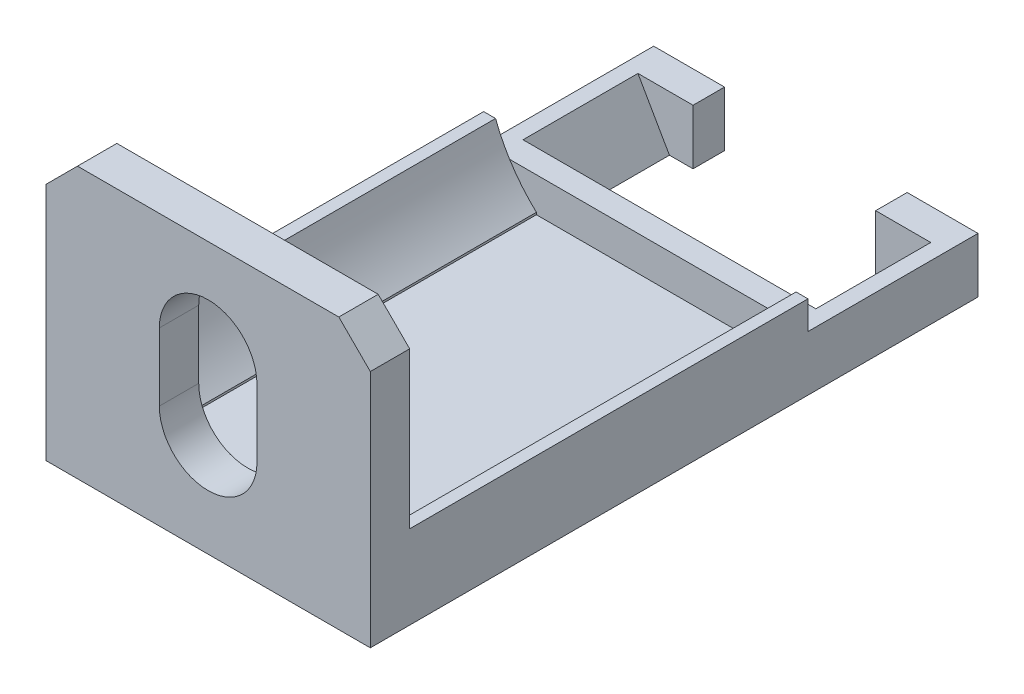
SolidWorks part; units mm, degrees
ref_plane "Front Plane" through (0, 0, 0) normal (0, 0, 1) x (1, 0, 0)
ref_plane "Top Plane" through (0, 0, 0) normal (0, 1, 0) x (1, 0, 0)
ref_plane "Right Plane" through (0, 0, 0) normal (1, 0, 0) x (0, 0, -1)
sketch "Sketch1" plane through (0, 0, 0) normal (0, 0, 1) x (1, 0, 0)
  line L0 (0, 0) -> (0, 8.6) construction
  line L1 (-10.3, -8.6) -> (10.3, -8.6)
  line L2 (-10.3, -8.6) -> (-10.3, 8.6)
  line L3 (-10.3, 8.6) -> (10.3, 8.6)
  line L4 (10.3, -8.6) -> (10.3, 8.6)
  line L5 (-10.3, -8.6) -> (10.3, 8.6) construction
  line L6 (-10.3, 8.6) -> (10.3, -8.6) construction
  line L7 (0, 2.3) -> (0, -2) construction
  line L8 (3.1, 2.3) -> (3.1, -2)
  line L9 (-3.1, 2.3) -> (-3.1, -2)
  arc A0 (3.1, 2.3) -> (-3.1, 2.3) centre (0, 2.3) ccw
  arc A1 (-3.1, -2) -> (3.1, -2) centre (0, -2) ccw
  point P0 (0, 0)
  point P10 (0, 0.15)
  dimension "D1" = 20.6
  dimension "D2" = 17.2
  dimension "D3" = 3.2
  dimension "D4" = 6.2
  dimension "D5" = 3.5
extrude "Boss-Extrude1" add sketch "Sketch1" along normal blind 2.5
sketch "Sketch2" plane through (0, 0, 0) normal (0, 0, -1) x (-1, 0, 0)
  line L0 (10.3, 8.6) -> (10.3, -8.6) construction
  line L1 (-10.3, -8.6) -> (10.3, -8.6)
  line L2 (-10.3, -8.6) -> (-10.3, -7.3)
  line L3 (-10.3, -7.3) -> (10.3, -7.3)
  line L4 (10.3, -8.6) -> (10.3, -7.3)
  dimension "D1" = 1.3
extrude "Boss-Extrude2" add sketch "Sketch2" along normal blind 25.3
sketch "Sketch3" plane through (0, 0, -25.3) normal (0, 0, -1) x (-1, 0, 0)
  line L0 (10.3, 8.6) -> (10.3, -7.3) construction
  line L1 (-10.3, -8.6) -> (10.3, -8.6)
  line L2 (-10.3, -8.6) -> (-10.3, -5.1)
  line L3 (-10.3, -5.1) -> (10.3, -5.1)
  line L4 (10.3, -8.6) -> (10.3, -5.1)
  dimension "D1" = 3.5
extrude "Boss-Extrude3" add sketch "Sketch3" along normal blind 1.5
sketch "Sketch4" plane through (0, -7.3, 0) normal (0, 1, 0) x (1, 0, 0)
  line L0 (0, 25.3) -> (0, 0) construction
  line L1 (-10.3, 25.3) -> (10.3, 25.3) construction
  line L3 (-6.95, 0) -> (6.95, 0)
  line L4 (-6.95, 0) -> (-6.95, 25.3)
  line L5 (-6.95, 25.3) -> (6.95, 25.3)
  line L6 (6.95, 0) -> (6.95, 25.3)
  line L7 (-6.95, 0) -> (6.95, 25.3) construction
  line L8 (-6.95, 25.3) -> (6.95, 0) construction
  line L9 (-10.3, 0) -> (10.3, 0)
  line L10 (-10.3, 0) -> (-10.3, 25.3)
  line L11 (-10.3, 25.3) -> (10.3, 25.3)
  line L12 (10.3, 0) -> (10.3, 25.3)
  line L13 (-10.3, 0) -> (10.3, 25.3) construction
  line L14 (-10.3, 25.3) -> (10.3, 0) construction
  point P5 (0, 12.65)
  point P10 (0, 12.65)
  line M9 (-10.3, 0) -> (10.3, 0)
  line M10 (10.3, 0) -> (10.3, 25.3)
  line M11 (10.3, 25.3) -> (-10.3, 25.3)
  line M12 (-10.3, 25.3) -> (-10.3, 0)
  dimension "D1" = 13.9
extrude "Boss-Extrude4" add sketch "Sketch4" along normal blind 4 contours L4 M9 M11 M12 | L6 M9 M10 M11
sketch "Sketch5" plane through (0, 0, 0) normal (0, 0, -1) x (-1, 0, 0)
  line L0 (6.95, -7.3) -> (-6.95, -7.3) construction
  line L1 (6.95, -7.3) -> (-6.95, -7.3)
  circle A0 centre (0, 0.3) radius 10.2
  point P5 (0, 0.7056)
  line M2 (-6.95, -3.3) -> (-6.95, -7.3)
  line M4 (6.95, -7.3) -> (6.95, -3.3)
  line M5 (6.95, -3.3) -> (10.3, -3.3)
  line M7 (10.3, 8.6) -> (-10.3, 8.6)
  line M9 (-10.3, -3.3) -> (-6.95, -3.3)
  line M10 (-3.1, -2) -> (-3.1, 2.3)
  arc M11 (-3.1, 2.3) -> (3.1, 2.3) centre (0, 2.3) cw
  line M12 (3.1, 2.3) -> (3.1, -2)
  arc M13 (3.1, -2) -> (-3.1, -2) centre (0, -2) cw
  dimension "D1" = 20.4
  dimension "D2" = 0.3
extrude "Cut-Extrude2" cut sketch "Sketch5" along normal up to surface (25.3 mm away) contours A0 L1 M7 M9 M2 M4 M5 M13 M10 M11 M12 | A0 M4 M5 | A0 M9 M2 up to face at (0, -6.2, -25.3)
chamfer "Chamfer1" distance 2 angle 45 2 edges at (-10.3, 8.6, 1.25) (10.3, 8.6, 1.25)
sketch "Sketch6" plane through (0, 0, -26.8) normal (0, 0, -1) x (-1, 0, 0)
  line L0 (-7.3, -8.6) -> (-10.3, -8.6)
  line L1 (-10.3, -8.6) -> (10.3, -8.6) construction
  line L2 (-10.3, -8.6) -> (-10.3, -5.1)
  line L3 (-10.3, -5.1) -> (-9.3, -5.1)
  line L4 (10.3, -5.1) -> (-10.3, -5.1) construction
  line L5 (-9.3, -5.1) -> (-7.3, -8.6)
  line L6 (0, -8.6) -> (0, 0) construction
  line L7 (9.3, -5.1) -> (7.3, -8.6)
  line L8 (10.3, -5.1) -> (9.3, -5.1)
  line L9 (10.3, -8.6) -> (10.3, -5.1)
  line L10 (7.3, -8.6) -> (10.3, -8.6)
  dimension "D1" = 3
  dimension "D2" = 1
extrude "Boss-Extrude5" add sketch "Sketch6" along normal blind 9.3
sketch "Sketch7" plane through (0, 0, -36.1) normal (0, 0, -1) x (-1, 0, 0)
  line L0 (0, -8.6) -> (0, 0) construction
  line L1 (-10.3, -8.6) -> (-5.8, -8.6)
  line L2 (-10.3, -8.6) -> (-10.3, -5.1)
  line L3 (-10.3, -5.1) -> (-5.8, -5.1)
  line L4 (-5.8, -8.6) -> (-5.8, -5.1)
  line L5 (-7.3, -8.6) -> (7.3, -8.6) construction
  line L6 (5.8, -8.6) -> (5.8, -5.1)
  line L7 (10.3, -5.1) -> (5.8, -5.1)
  line L8 (10.3, -8.6) -> (10.3, -5.1)
  line L9 (10.3, -8.6) -> (5.8, -8.6)
  dimension "D1" = 4.5
extrude "Boss-Extrude6" add sketch "Sketch7" against normal blind 2
